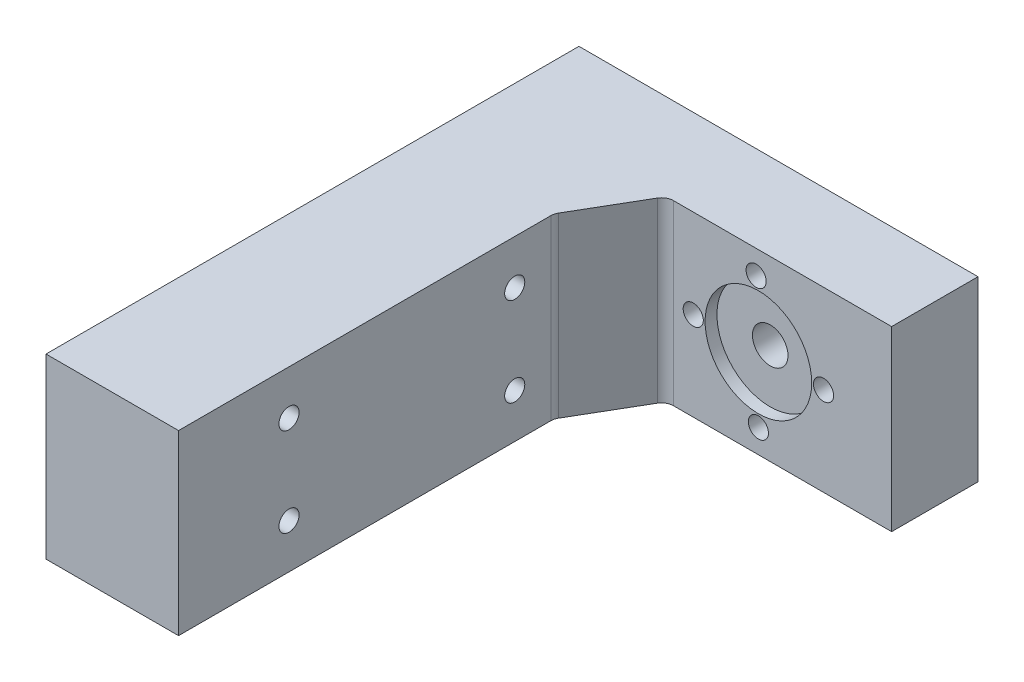
SolidWorks part; units mm, degrees
ref_plane "Front Plane" through (0, 0, 0) normal (1, 0, 0) x (0, 1, 0)
ref_plane "Top Plane" through (0, 0, 0) normal (0, 0, 1) x (0, 1, 0)
ref_plane "Right Plane" through (0, 0, 0) normal (0, 1, 0) x (-1, 0, 0)
sketch "Sketch2" plane through (0, 0, 0) normal (0, 1, 0) x (-1, 0, 0)
  line L0 (0, 0) -> (673.8533, 0)
  line L1 (673.8533, 0) -> (673.8533, 900)
  line L2 (673.8533, 900) -> (450, 900)
  line L3 (450, 900) -> (450, 145.8433)
  line L4 (450, 145.8433) -> (0, 145.8433)
  line L5 (0, 145.8433) -> (0, 0)
  dimension "D1" = 223.8533
  dimension "D3" = 145.8433
  dimension "D4" = 900
  dimension "D2" = 450
extrude "Boss-Extrude1" add sketch "Sketch2" along normal blind 300
sketch "Sketch3" plane through (0, 0, 145.8433) normal (0, 0, 1) x (1, 0, 0)
  circle A0 centre (-225, 150) radius 110 construction
  circle A1 centre (-335, 150) radius 17
  circle A2 centre (-228.823, 259.9335) radius 17
  circle A3 centre (-115, 150) radius 17
  circle A4 centre (-225, 40) radius 17
  circle A5 centre (-225, 150) radius 30
  dimension "D2" = 34
  dimension "D3" = 220
  dimension "D4" = 60
  dimension "D1" = 150
extrude "Cut-Extrude1" cut sketch "Sketch3" against normal through all
sketch "Sketch4" plane through (0, 0, 145.8433) normal (0, 0, 1) x (1, 0, 0)
  circle A0 centre (-225, 150) radius 90
  dimension "D1" = 180
extrude "Cut-Extrude2" cut sketch "Sketch4" against normal blind 20
sketch "Sketch5" plane through (-450, 0, 0) normal (1, 0, 0) x (0, 1, 0)
  circle A0 centre (75, 713.5) radius 17
  circle A1 centre (225, 713.5) radius 17
  circle A2 centre (75, 332.3433) radius 17
  circle A3 centre (225, 332.3433) radius 17
  dimension "D5" = 34
  dimension "D1" = 75
  dimension "D2" = 186.5
  dimension "D3" = 186.5
  dimension "D4" = 75
extrude "Cut-Extrude3" cut sketch "Sketch5" against normal through all
fillet "Chamfer1" radius 120 1 edges at (-450, 150, 145.8433)
fillet "Fillet1" radius 20 2 edges at (-450, 150, 265.8433) (-380, 150, 145.8433)
scale "Scale1" scale about centroid uniform scaling yes scale factor 0.1
equation "\"b\"= 30'Base dimensions for Mount (mm)"
equation "\"L1\"= 45'Height of Feature 1 (mm)"
equation "\"s\"= 18'Distance of Force from Feature 1 (mm)"
equation "\"FOS\"= 3'Given Factor of Safety"
equation "\"defl\"= 0.3'Given Deflection (mm)"
equation "\"E\"= 2350'Modulus of Elasticity (N/mm^2)"
equation "\"Yield\"= 45.2'Yield Stress of PLA Plastic (N/mm^2)"
equation "\"P\"= 300'Force Applied (N)"
equation "\"M_1\"= \"P\" * \"s\"'Moment applied to Feature 1 (N mm)"
equation "\"h1\"= ( ( 6 * \"M_1\" * ( \"L1\" ^ 2 ) ) / ( \"defl\" * \"b\" * \"E\" ) ) ^ ( 1 / 3 )'Height of Feature 1 (mm)"
equation "\"L_t\"= IIF ( ( ( \"h1\" + \"L_m\" ) - int ( \"h1\" + \"L_m\" ) ) > 0 , int ( \"h1\" + \"L_m\" ) + 1 , \"h1\" + \"L_m\" )'Length of Feature 2 (mm) (rounded with up with if statement)"
equation "\"L_m\"= 74.6'Length of Motor given (mm)"
equation "\"B_h\"= \"L_m\" / 4'Bolt Distance from vertical edges (mm)"
equation "\"B_w\"= \"b\" / 4'Bolt Distance from Horizontal edges (mm)"
equation "\"L_f\"= \"B_h\" + \"h1\" + ( \"4_M3\" / 2 )'Length of Feature 2 Free Part (mm)"
equation "\"M_2\"= \"P\" * ( \"L_t\" + \"s\" )'Moment applied to Feature 2 (N mm)"
equation "\"h2\"= ( ( 6 * \"M_2\" * ( \"L_f\" ^ 2 ) ) / ( \"defl\" * \"b\" * \"E\" ) ) ^ ( 1 / 3 )'Height of Feature 2 (N mm)"
equation "\"D1@Sketch2\"=\"h2\""
equation "\"D3@Sketch2\"=\"h1\""
equation "\"D4@Sketch2\"=\"L_t\""
equation "\"D1@Boss-Extrude1\"=\"b\""
equation "\"D2@Sketch2\"=\"L1\""
equation "\"D1@Sketch3\"=\"b\"/2"
equation "\"4_M3\"= 3.4'Diameter of Mounting Holes (mm)"
equation "\"D2@Sketch3\"=\"4_M3\""
equation "\"D1@Sketch5\"=\"B_w\""
equation "\"D2@Sketch5\"=\"B_h\""
equation "\"D3@Sketch5\"=\"B_h\""
equation "\"D4@Sketch5\"=\"B_w\""
equation "\"D5@Sketch5\"=\"4_M3\""
